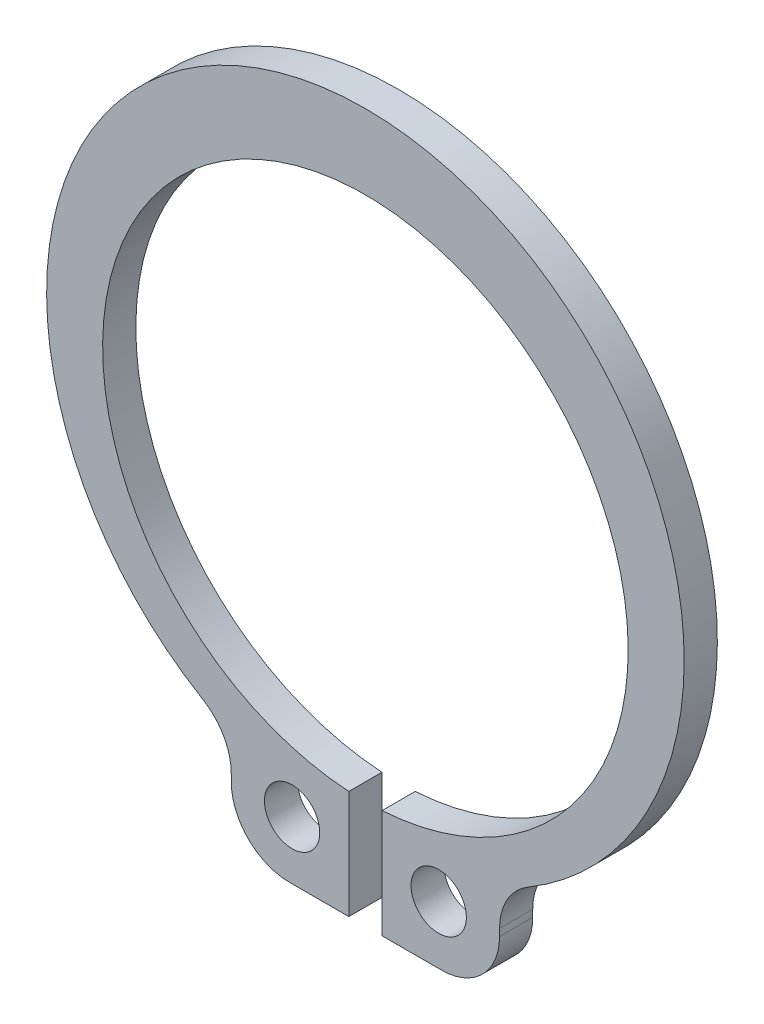
SolidWorks part; units mm, degrees
ref_plane "Front Plane" through (0, 0, 0) normal (0, 0, 1) x (1, 0, 0)
ref_plane "Top Plane" through (0, 0, 0) normal (0, 1, 0) x (1, 0, 0)
ref_plane "Right Plane" through (0, 0, 0) normal (1, 0, 0) x (0, 0, -1)
sketch "Sketch1" plane through (0, 0, 0) normal (0, 0, 1) x (1, 0, 0)
  line L0 (-4.85, -9.7798) -> (-4.85, -13.4)
  line L1 (-4.85, -13.4) -> (-0.6, -13.4)
  line L5 (-0.6, -13.4) -> (-0.6, -9.481)
  line L6 (0.6, -9.481) -> (0.6, -13.4)
  line L10 (0.6, -13.4) -> (4.85, -13.4)
  line L11 (4.85, -13.4) -> (4.85, -9.7798)
  line L12 (0, 0) -> (0, 12.2) construction
  arc A0 (4.85, -9.7798) -> (-4.85, -9.7798) centre (0, 0.675) ccw
  arc A4 (-0.6, -9.481) -> (0.6, -9.481) centre (0, 0) cw
  dimension "D2_s" = 19
  dimension "MSM_1" = 23.05
  dimension "MSM_2" = 9.7
  dimension "A_s" = 3.9
  dimension "MSM_5" = 1.2
  dimension "FIX_4" = 0.675
  dimension "B_s" = 2.7
extrude "Boss-Extrude1" add sketch "Sketch1" along normal blind 1.2
sketch "Sketch2" plane through (0, 0, 0) normal (0, 0, -1) x (-1, 0, 0)
  line L0 (4.85, -11.3) -> (-4.85, -11.3) construction
  line L1 (4.85, -13.4) -> (4.85, -9.7798) construction
  line L2 (-4.85, -9.7798) -> (-4.85, -13.4) construction
  line L3 (4.85, -13.4) -> (0.6, -13.4) construction
  line L4 (0, 0) -> (0, -13.4) construction
  circle A0 centre (-2.65, -11.3) radius 1
  circle A1 centre (2.65, -11.3) radius 1
  dimension "D0_s" = 2
  dimension "MSM_4" = 2.1
  dimension "MSM_3" = 5.3
extrude "Cut-Extrude1" cut sketch "Sketch2" against normal through all
fillet "Fillet1" radius 2.1 2 edges at (4.85, -9.7798, 0.6) (-4.85, -9.7798, 0.6)
fillet "Fillet2" radius 2.1 2 edges at (4.85, -13.4, 0.6) (-4.85, -13.4, 0.6)
other "DeleteFace1" [suppressed]
sketch "Sketch3" [suppressed] plane through (0, 0, 0) normal (0, 0, -1) x (-1, 0, 0)
  line L0 (3.8, -6.3) -> (-3.8, -6.3) construction
  line L4 (0, 0) -> (0, -7.8) construction
  line L5 (-0.15, -7.8) -> (-2.2, -7.8) construction
  line L7 (-2.15, -5.7) -> (2.15, -5.7)
  line L8 (2.15, -6.9) -> (-2.15, -6.9)
  line L9 (3.8, -6.2) -> (3.8, -4.6266) construction
  line L10 (-3.8, -4.6266) -> (-3.8, -6.2) construction
  arc A0 (-2.15, -5.7) -> (-2.15, -6.9) centre (-2.15, -6.3) ccw
  arc A1 (2.15, -6.9) -> (2.15, -5.7) centre (2.15, -6.3) ccw
  point P1 (0, -6.3)
  dimension "D0_s" = 2
  dimension "MSM_3" = 5.3
  dimension "MSM_4" = 2.1
extrude "Cut-Extrude2" [suppressed] cut sketch "Sketch3" against normal through all
equation "\"No.8 or Less\"= IIF ( \"T_s\" < 1 , \"unsuppressed\" , \"suppressed\" )"
